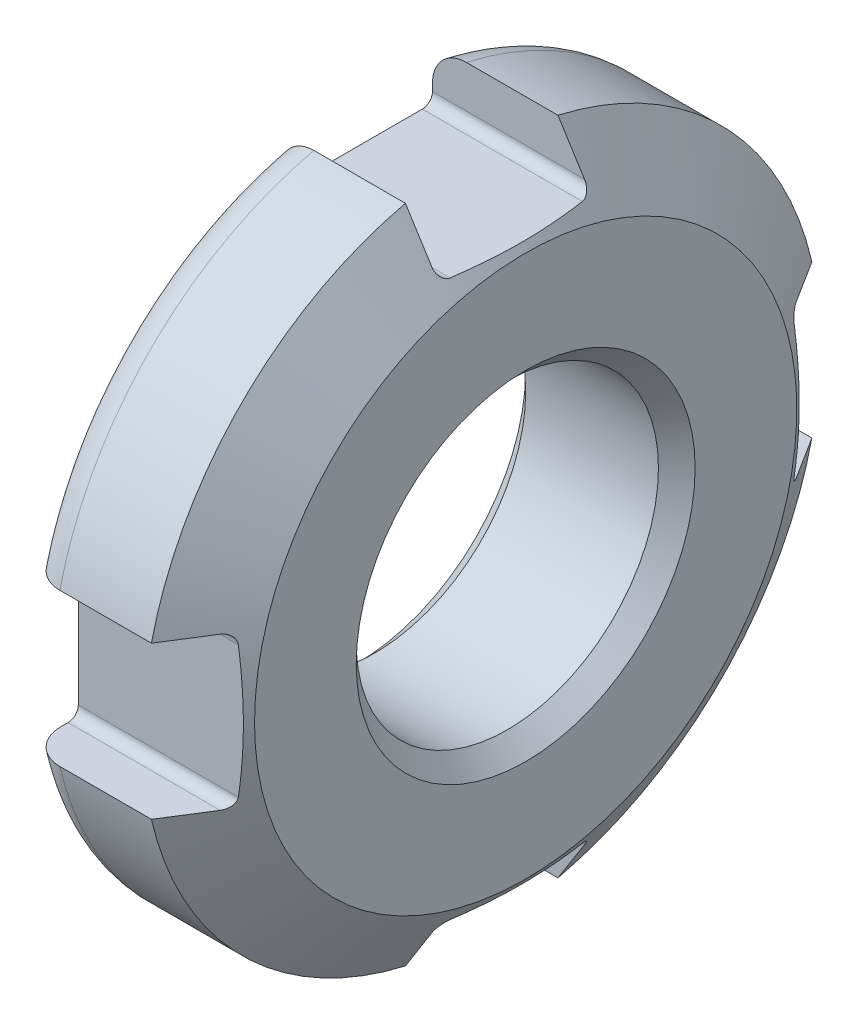
SolidWorks part; units mm, degrees
ref_plane "Front Plane" through (0, 0, 0) normal (0, 0, 1) x (1, 0, 0)
ref_plane "Top Plane" through (0, 0, 0) normal (0, 1, 0) x (1, 0, 0)
ref_plane "Right Plane" through (0, 0, 0) normal (1, 0, 0) x (0, 0, -1)
ref_plane "Plane1" through (0, 0, 0) normal (0, 0, -1) x (-1, 0, 0)
sketch "Sketch1" plane through (0, 0, 0) normal (0, 0, -1) x (-1, 0, 0)
  line L0 (-5, 8) -> (-5, 0)
  line L1 (-5, 0) -> (0, 0)
  line L2 (0, 0) -> (0, 10)
  line L3 (0, 10) -> (-3.7012, 10)
  line L4 (-3.7012, 10) -> (-5, 8)
  line L5 (-5, 0) -> (0, 0) construction
revolve "Revolve1" add sketch "Sketch1" angle 360 about L5
sketch "Sketch2" plane through (0, 0, 0) normal (-1, 0, 0) x (0, 0, 1)
  line L0 (9.7436, 2.25) -> (8.2, 2.25)
  line L1 (8.2, 2.25) -> (8.2, -2.25)
  line L2 (8.2, -2.25) -> (9.7436, -2.25)
  arc A0 (9.7436, -2.25) -> (9.7436, 2.25) centre (0, 0) ccw
extrude "Cut-Extrude1" cut sketch "Sketch2" against normal up to next
sketch "Sketch3" plane through (0, 0, 0) normal (-1, 0, 0) x (0, 0, 1)
  line L0 (2.25, -9.7436) -> (2.25, -8.2)
  line L1 (2.25, -8.2) -> (-2.25, -8.2)
  line L2 (-2.25, -8.2) -> (-2.25, -9.7436)
  arc A0 (-2.25, -9.7436) -> (2.25, -9.7436) centre (0, 0) ccw
extrude "Cut-Extrude2" cut sketch "Sketch3" against normal up to next
sketch "Sketch4" plane through (0, 0, 0) normal (-1, 0, 0) x (0, 0, 1)
  line L0 (-9.7436, -2.25) -> (-8.2, -2.25)
  line L1 (-8.2, -2.25) -> (-8.2, 2.25)
  line L2 (-8.2, 2.25) -> (-9.7436, 2.25)
  arc A0 (-9.7436, 2.25) -> (-9.7436, -2.25) centre (0, 0) ccw
extrude "Cut-Extrude3" cut sketch "Sketch4" against normal up to next
sketch "Sketch5" plane through (0, 0, 0) normal (-1, 0, 0) x (0, 0, 1)
  line L0 (-2.25, 9.7436) -> (-2.25, 8.2)
  line L1 (-2.25, 8.2) -> (2.25, 8.2)
  line L2 (2.25, 8.2) -> (2.25, 9.7436)
  arc A0 (2.25, 9.7436) -> (-2.25, 9.7436) centre (0, 0) ccw
extrude "Cut-Extrude4" cut sketch "Sketch5" against normal up to next
hole_wizard "M8 Clearance Hole1" positions "Sketch7" profile "Sketch6" hole size "M8" standard "ANSI Metric"
sketch "Sketch7" plane through (5, 0, 0) normal (1, 0, 0) x (0, 0, -1)
  point P0 (0, 0)
sketch "Sketch6" plane through (5, 0, 0) normal (0, 1, 0) x (0, 0, -1)
  line L0 (0, 0) -> (0, 5)
  line L1 (0, 5) -> (4.4585, 5)
  line L2 (4.4585, 5) -> (4.4585, 0)
  line L5 (4.4585, 0) -> (0, 0)
  line L11 (0, -6.35) -> (0, 107.95) construction
  dimension "Thru Hole Dia." = 8.917
  dimension "Thru Hole Depth" = 5
chamfer "Chamfer1" distance 0.5415 angle 45 2 edges at (0, 0, -4.4585) (5, 0, -4.4585)
fillet "Fillet1" radius 0.3 8 edges at (2.3366, 8.2, -2.25) (2.3366, 2.25, 8.2) (2.3366, -8.2, 2.25) (2.3366, -2.25, 8.2) (2.3366, 8.2, 2.25) (2.3366, -8.2, -2.25) (2.3366, 2.25, -8.2) (2.3366, -2.25, -8.2)
fillet "Fillet2" radius 1 4 edges at (0, 7.0711, 7.0711) (0, 7.0711, -7.0711) (0, -7.0711, 7.0711) (0, -7.0711, -7.0711)
